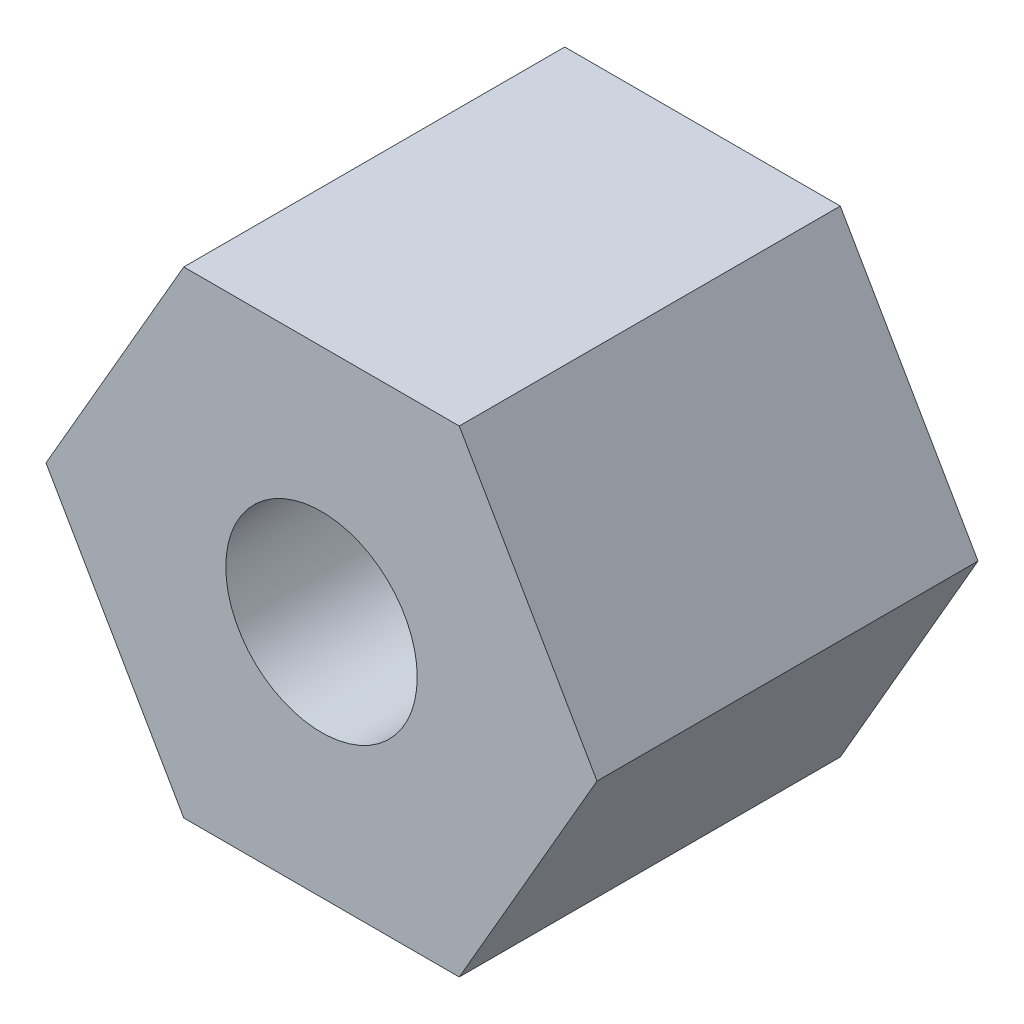
SolidWorks part; units mm, degrees
ref_plane "前视基准面" through (0, 0, 0) normal (0, 0, 1) x (1, 0, 0)
ref_plane "上视基准面" through (0, 0, 0) normal (0, 1, 0) x (1, 0, 0)
ref_plane "右视基准面" through (0, 0, 0) normal (1, 0, 0) x (0, 0, -1)
sketch "草图1" plane through (0, 0, 0) normal (0, 0, 1) x (1, 0, 0)
  line L1 (14.4626, 25.05) -> (-14.4626, 25.05)
  line L2 (-14.4626, 25.05) -> (-28.9252, 0)
  line L3 (-28.9252, 0) -> (-14.4626, -25.05)
  line L4 (-14.4626, -25.05) -> (14.4626, -25.05)
  line L5 (14.4626, -25.05) -> (28.9252, 0)
  line L6 (28.9252, 0) -> (14.4626, 25.05)
  circle A0 centre (0, 0) radius 10.05
  circle A1 centre (0, 0) radius 25.05 construction
  circle A2 centre (0, 0) radius 25.05 construction
  dimension "D1" = 15
  dimension "D2" = 20.1
extrude "凸台-拉伸1" add sketch "草图1" along normal blind 40
